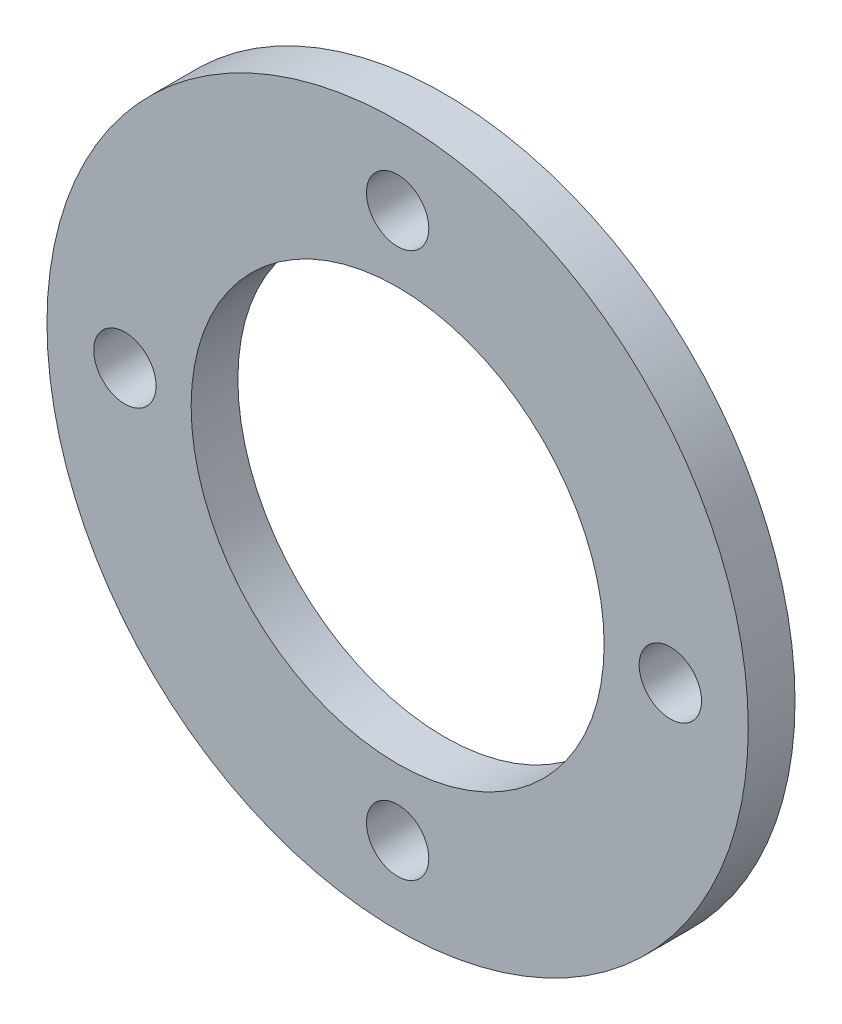
SolidWorks part; units mm, degrees
material "A-玻璃纤维"
ref_plane "前视基准面" through (0, 0, 0) normal (0, 0, 1) x (1, 0, 0)
ref_plane "上视基准面" through (0, 0, 0) normal (0, 1, 0) x (1, 0, 0)
ref_plane "右视基准面" through (0, 0, 0) normal (1, 0, 0) x (0, 0, -1)
sketch "草图1" plane through (0, 0, 0) normal (0, 0, 1) x (1, 0, 0)
  circle A0 centre (0, 0) radius 22.5
  circle A1 centre (0, 0) radius 13.25
  circle A2 centre (0, 0) radius 17.5 construction
  circle A3 centre (0, 17.5) radius 2
  circle A4 centre (-17.5, 0) radius 2
  circle A5 centre (0, -17.5) radius 2
  circle A6 centre (17.5, 0) radius 2
  dimension "D1" = 26.5
  dimension "D2" = 45
  dimension "D3" = 35
  dimension "D4" = 4
extrude "凸台-拉伸1" add sketch "草图1" along normal blind 3
